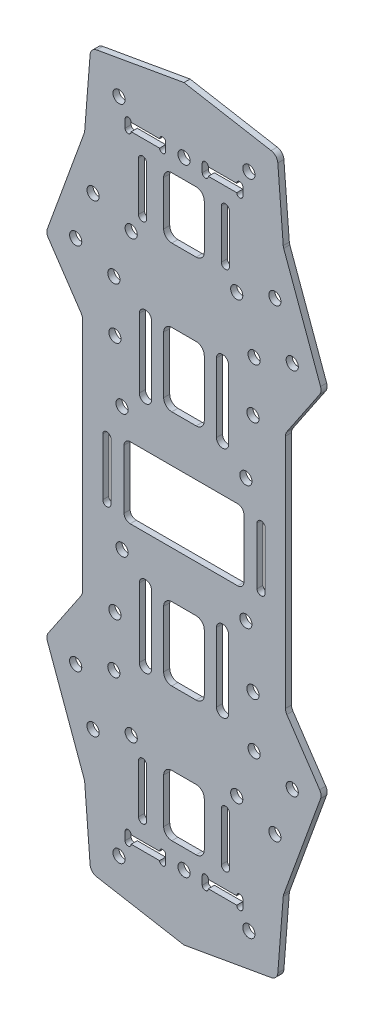
SolidWorks part; units mm, degrees
ref_plane "Front Plane" through (0, 0, 0) normal (0, 0, 1) x (1, 0, 0)
ref_plane "Top Plane" through (0, 0, 0) normal (0, 1, 0) x (1, 0, 0)
ref_plane "Right Plane" through (0, 0, 0) normal (1, 0, 0) x (0, 0, -1)
sketch "Sketch1" plane through (0, 0, 0) normal (0, 0, 1) x (1, 0, 0)
  line L0 (20, 7) -> (20, -7)
  line L1 (18, -7) -> (18, 7)
  line L2 (-18, 7) -> (-18, -7)
  line L3 (-20, -7) -> (-20, 7)
  line L4 (-11.2, -70.25) -> (-11.2, -58.25)
  line L5 (-9.2, -58.25) -> (-9.2, -70.25)
  line L6 (-11, -37.25) -> (-11, -20.25)
  line L7 (-8, -20.25) -> (-8, -37.25)
  line L8 (8, -37.25) -> (8, -20.25)
  line L9 (11, -20.25) -> (11, -37.25)
  line L10 (9.2, -70.25) -> (9.2, -58.25)
  line L11 (11.2, -58.25) -> (11.2, -70.25)
  line L12 (-3, -20.25) -> (3, -20.25)
  line L13 (5, -22.25) -> (5, -36.25)
  line L14 (3, -38.25) -> (-3, -38.25)
  line L15 (-5, -36.25) -> (-5, -22.25)
  line L16 (5, -58.25) -> (5, -69.25)
  line L17 (3, -71.25) -> (-3, -71.25)
  line L18 (-5, -69.25) -> (-5, -58.25)
  line L19 (-3, -56.25) -> (3, -56.25)
  line L20 (11.2, 70.25) -> (11.2, 58.25)
  line L21 (9.2, 58.25) -> (9.2, 70.25)
  line L22 (11, 37.25) -> (11, 20.25)
  line L23 (8, 20.25) -> (8, 37.25)
  line L24 (-8, 37.25) -> (-8, 20.25)
  line L25 (-11, 20.25) -> (-11, 37.25)
  line L26 (-9.2, 70.25) -> (-9.2, 58.25)
  line L27 (-11.2, 58.25) -> (-11.2, 70.25)
  line L28 (13.25, -8.75) -> (-13.25, -8.75)
  line L29 (-14.75, -7.25) -> (-14.75, 7.25)
  line L30 (-13.25, 8.75) -> (13.25, 8.75)
  line L31 (14.75, 7.25) -> (14.75, -7.25)
  line L32 (-5, 58.25) -> (-5, 69.25)
  line L33 (-3, 71.25) -> (3, 71.25)
  line L34 (5, 69.25) -> (5, 58.25)
  line L35 (3, 56.25) -> (-3, 56.25)
  line L36 (-3, 38.25) -> (3, 38.25)
  line L37 (5, 36.25) -> (5, 22.25)
  line L38 (3, 20.25) -> (-3, 20.25)
  line L39 (-5, 22.25) -> (-5, 36.25)
  line L40 (-24.5714, 68.9048) -> (-33.6515, 43.9576)
  line L41 (-33.4302, 42.1552) -> (-25.3419, 30.1639)
  line L42 (-25, 29.0455) -> (-25, -29.0455)
  line L43 (-25.3419, -30.1639) -> (-33.4302, -42.1552)
  line L44 (-33.6515, -43.9576) -> (-24.5714, -68.9048)
  line L45 (-24.457, -69.4319) -> (-23.1215, -86.4007)
  line L46 (-21.475, -88.2134) -> (0, -92)
  line L47 (0, -92) -> (21.475, -88.2134)
  line L48 (23.1215, -86.4007) -> (24.457, -69.4319)
  line L49 (24.5714, -68.9048) -> (33.6515, -43.9576)
  line L50 (33.4302, -42.1552) -> (25.3419, -30.1639)
  line L51 (25, -29.0455) -> (25, 29.0455)
  line L52 (25.3419, 30.1639) -> (33.4302, 42.1552)
  line L53 (33.6515, 43.9576) -> (24.5714, 68.9048)
  line L54 (24.457, 69.4319) -> (23.1215, 86.4007)
  line L55 (21.475, 88.2134) -> (0, 92)
  line L56 (0, 92) -> (-21.475, 88.2134)
  line L57 (-23.1215, 86.4007) -> (-24.457, 69.4319)
  line L58 (-14.5, 75) -> (-14.5, 77)
  line L59 (-13, 77) -> (-6, 77)
  line L60 (-4.5, 77) -> (-4.5, 75)
  line L61 (-6, 75) -> (-13, 75)
  line L62 (6, 77) -> (13, 77)
  line L63 (14.5, 77) -> (14.5, 75)
  line L64 (13, 75) -> (6, 75)
  line L65 (4.5, 75) -> (4.5, 77)
  line L66 (13, -77) -> (6, -77)
  line L67 (4.5, -77) -> (4.5, -75)
  line L68 (6, -75) -> (13, -75)
  line L69 (14.5, -75) -> (14.5, -77)
  line L70 (-6, -77) -> (-13, -77)
  line L71 (-14.5, -77) -> (-14.5, -75)
  line L72 (-13, -75) -> (-6, -75)
  line L73 (-4.5, -75) -> (-4.5, -77)
  arc A0 (20, -7) -> (18, -7) centre (19, -7) cw
  arc A1 (18, 7) -> (20, 7) centre (19, 7) cw
  arc A2 (-18, -7) -> (-20, -7) centre (-19, -7) cw
  arc A3 (-20, 7) -> (-18, 7) centre (-19, 7) cw
  arc A4 (-11.2, -58.25) -> (-9.2, -58.25) centre (-10.2, -58.25) cw
  arc A5 (-9.2, -70.25) -> (-11.2, -70.25) centre (-10.2, -70.25) cw
  arc A6 (-11, -20.25) -> (-8, -20.25) centre (-9.5, -20.25) cw
  arc A7 (-8, -37.25) -> (-11, -37.25) centre (-9.5, -37.25) cw
  arc A8 (8, -20.25) -> (11, -20.25) centre (9.5, -20.25) cw
  arc A9 (11, -37.25) -> (8, -37.25) centre (9.5, -37.25) cw
  arc A10 (9.2, -58.25) -> (11.2, -58.25) centre (10.2, -58.25) cw
  arc A11 (11.2, -70.25) -> (9.2, -70.25) centre (10.2, -70.25) cw
  arc A12 (3, -20.25) -> (5, -22.25) centre (3, -22.25) cw
  arc A13 (5, -36.25) -> (3, -38.25) centre (3, -36.25) cw
  arc A14 (-3, -38.25) -> (-5, -36.25) centre (-3, -36.25) cw
  arc A15 (-5, -22.25) -> (-3, -20.25) centre (-3, -22.25) cw
  arc A16 (5, -69.25) -> (3, -71.25) centre (3, -69.25) cw
  arc A17 (-3, -71.25) -> (-5, -69.25) centre (-3, -69.25) cw
  arc A18 (-5, -58.25) -> (-3, -56.25) centre (-3, -58.25) cw
  arc A19 (3, -56.25) -> (5, -58.25) centre (3, -58.25) cw
  arc A20 (11.2, 58.25) -> (9.2, 58.25) centre (10.2, 58.25) cw
  arc A21 (9.2, 70.25) -> (11.2, 70.25) centre (10.2, 70.25) cw
  arc A22 (11, 20.25) -> (8, 20.25) centre (9.5, 20.25) cw
  arc A23 (8, 37.25) -> (11, 37.25) centre (9.5, 37.25) cw
  arc A24 (-8, 20.25) -> (-11, 20.25) centre (-9.5, 20.25) cw
  arc A25 (-11, 37.25) -> (-8, 37.25) centre (-9.5, 37.25) cw
  arc A26 (-9.2, 58.25) -> (-11.2, 58.25) centre (-10.2, 58.25) cw
  arc A27 (-11.2, 70.25) -> (-9.2, 70.25) centre (-10.2, 70.25) cw
  arc A28 (-13.25, -8.75) -> (-14.75, -7.25) centre (-13.25, -7.25) cw
  arc A29 (-14.75, 7.25) -> (-13.25, 8.75) centre (-13.25, 7.25) cw
  arc A30 (13.25, 8.75) -> (14.75, 7.25) centre (13.25, 7.25) cw
  arc A31 (14.75, -7.25) -> (13.25, -8.75) centre (13.25, -7.25) cw
  arc A32 (-5, 69.25) -> (-3, 71.25) centre (-3, 69.25) cw
  arc A33 (3, 71.25) -> (5, 69.25) centre (3, 69.25) cw
  arc A34 (5, 58.25) -> (3, 56.25) centre (3, 58.25) cw
  arc A35 (-3, 56.25) -> (-5, 58.25) centre (-3, 58.25) cw
  arc A36 (3, 38.25) -> (5, 36.25) centre (3, 36.25) cw
  arc A37 (5, 22.25) -> (3, 20.25) centre (3, 22.25) cw
  arc A38 (-3, 20.25) -> (-5, 22.25) centre (-3, 22.25) cw
  arc A39 (-5, 36.25) -> (-3, 38.25) centre (-3, 36.25) cw
  arc A40 (-24.457, 69.4319) -> (-24.5714, 68.9048) centre (-26.4508, 69.5889) cw
  arc A41 (-33.6515, 43.9576) -> (-33.4302, 42.1552) centre (-31.7721, 43.2736) ccw
  arc A42 (-25.3419, 30.1639) -> (-25, 29.0455) centre (-27, 29.0455) cw
  arc A43 (-25, -29.0455) -> (-25.3419, -30.1639) centre (-27, -29.0455) cw
  arc A44 (-33.4302, -42.1552) -> (-33.6515, -43.9576) centre (-31.7721, -43.2736) ccw
  arc A45 (-24.5714, -68.9048) -> (-24.457, -69.4319) centre (-26.4508, -69.5889) cw
  arc A46 (-23.1215, -86.4007) -> (-21.475, -88.2134) centre (-21.1277, -86.2438) ccw
  arc A47 (21.475, -88.2134) -> (23.1215, -86.4007) centre (21.1277, -86.2438) ccw
  arc A48 (24.457, -69.4319) -> (24.5714, -68.9048) centre (26.4508, -69.5889) cw
  arc A49 (33.6515, -43.9576) -> (33.4302, -42.1552) centre (31.7721, -43.2736) ccw
  arc A50 (25.3419, -30.1639) -> (25, -29.0455) centre (27, -29.0455) cw
  arc A51 (25, 29.0455) -> (25.3419, 30.1639) centre (27, 29.0455) cw
  arc A52 (33.4302, 42.1552) -> (33.6515, 43.9576) centre (31.7721, 43.2736) ccw
  arc A53 (24.5714, 68.9048) -> (24.457, 69.4319) centre (26.4508, 69.5889) cw
  arc A54 (23.1215, 86.4007) -> (21.475, 88.2134) centre (21.1277, 86.2438) ccw
  arc A55 (-21.475, 88.2134) -> (-23.1215, 86.4007) centre (-21.1277, 86.2438) ccw
  circle A56 centre (-16, 81) radius 1.5
  circle A57 centre (0, 76) radius 1.5
  circle A58 centre (-26.6722, 45.4202) radius 1.5
  circle A59 centre (-22.3969, 57.1664) radius 1.5
  circle A60 centre (-17.2753, 42) radius 1.5
  circle A61 centre (-13, 53.7462) radius 1.5
  circle A62 centre (-17, 29.5) radius 1.5
  circle A63 centre (-15.25, 15.25) radius 1.5
  circle A64 centre (15.25, 15.25) radius 1.5
  circle A65 centre (17, 29.5) radius 1.5
  circle A66 centre (13, 53.7462) radius 1.5
  circle A67 centre (17.2753, 42) radius 1.5
  circle A68 centre (22.3969, 57.1664) radius 1.5
  circle A69 centre (26.6722, 45.4202) radius 1.5
  circle A70 centre (16, 81) radius 1.5
  circle A71 centre (16, -81) radius 1.5
  circle A72 centre (26.6722, -45.4202) radius 1.5
  circle A73 centre (22.3969, -57.1664) radius 1.5
  circle A74 centre (17.2753, -42) radius 1.5
  circle A75 centre (13, -53.7462) radius 1.5
  circle A76 centre (17, -29.5) radius 1.5
  circle A77 centre (15.25, -15.25) radius 1.5
  circle A78 centre (-15.25, -15.25) radius 1.5
  circle A79 centre (-17, -29.5) radius 1.5
  circle A80 centre (-13, -53.7462) radius 1.5
  circle A81 centre (-17.2753, -42) radius 1.5
  circle A82 centre (-22.3969, -57.1664) radius 1.5
  circle A83 centre (-26.6722, -45.4202) radius 1.5
  circle A84 centre (0, -76) radius 1.5
  circle A85 centre (-16, -81) radius 1.5
  arc A86 (-13, 75) -> (-14.5, 75) centre (-13.75, 75) cw
  arc A87 (-14.5, 77) -> (-13, 77) centre (-13.75, 77) cw
  arc A88 (-6, 77) -> (-4.5, 77) centre (-5.25, 77) cw
  arc A89 (-4.5, 75) -> (-6, 75) centre (-5.25, 75) cw
  arc A90 (4.5, 77) -> (6, 77) centre (5.25, 77) cw
  arc A91 (13, 77) -> (14.5, 77) centre (13.75, 77) cw
  arc A92 (14.5, 75) -> (13, 75) centre (13.75, 75) cw
  arc A93 (6, 75) -> (4.5, 75) centre (5.25, 75) cw
  arc A94 (14.5, -77) -> (13, -77) centre (13.75, -77) cw
  arc A95 (6, -77) -> (4.5, -77) centre (5.25, -77) cw
  arc A96 (4.5, -75) -> (6, -75) centre (5.25, -75) cw
  arc A97 (13, -75) -> (14.5, -75) centre (13.75, -75) cw
  arc A98 (-4.5, -77) -> (-6, -77) centre (-5.25, -77) cw
  arc A99 (-13, -77) -> (-14.5, -77) centre (-13.75, -77) cw
  arc A100 (-14.5, -75) -> (-13, -75) centre (-13.75, -75) cw
  arc A101 (-6, -75) -> (-4.5, -75) centre (-5.25, -75) cw
extrude "bottom-plate" add sketch "Sketch1" against normal blind 1.5
